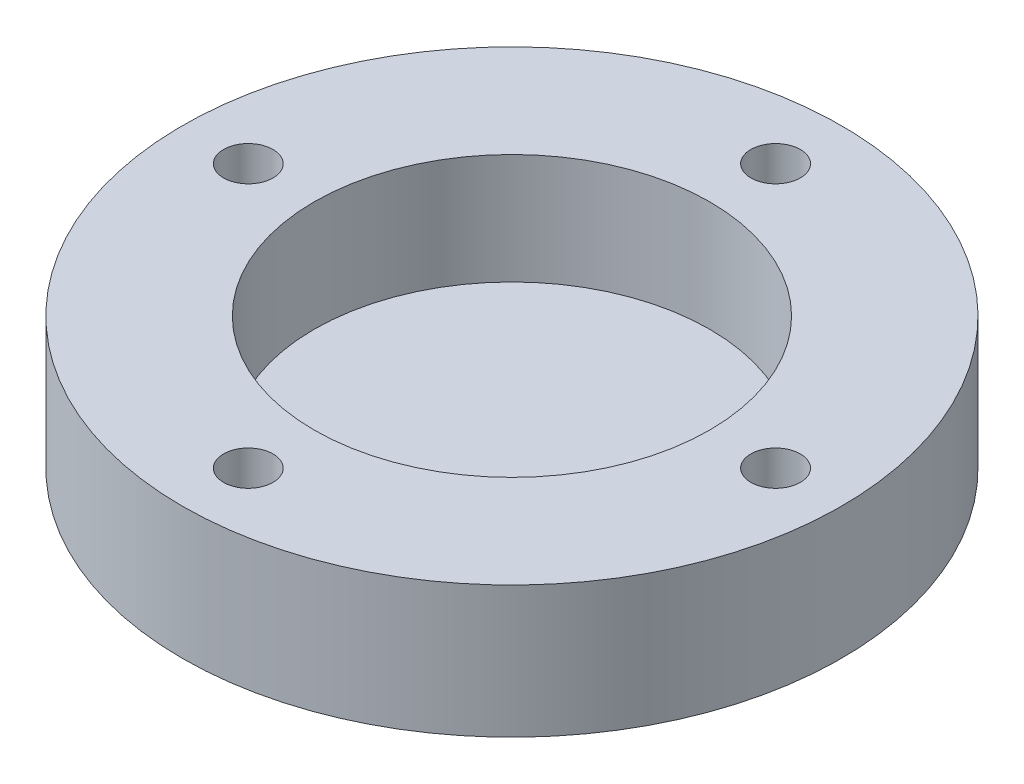
SolidWorks part; units mm, degrees
ref_plane "Front Plane" through (0, 0, 0) normal (0, 0, 1) x (1, 0, 0)
ref_plane "Top Plane" through (0, 0, 0) normal (0, 1, 0) x (1, 0, 0)
ref_plane "Right Plane" through (0, 0, 0) normal (1, 0, 0) x (0, 0, -1)
sketch "Sketch2" plane through (0, 0, 0) normal (0, 1, 0) x (1, 0, 0)
  circle A0 centre (0, 0) radius 20
  dimension "D1" = 40
extrude "Boss-Extrude1" add sketch "Sketch2" along normal blind 8
sketch "Sketch3" plane through (0, 8, 0) normal (0, 1, 0) x (1, 0, 0)
  line L0 (0, 0) -> (0, 16) construction
  line L1 (0, 36.0452) -> (0, 0) construction
  line L2 (0, 0) -> (29.8804, 0) construction
  line L3 (-16, 0) -> (0, 0) construction
  line L4 (16, 0) -> (0, 0) construction
  line L5 (0, 16) -> (0, 0) construction
  line L6 (0, 0) -> (0, -16) construction
  circle A1 centre (0, 16) radius 1.5
  circle A2 centre (-16, 0) radius 1.5
  circle A3 centre (16, 0) radius 1.5
  circle A4 centre (0, -16) radius 1.5
  dimension "D2" = 3
  dimension "D3" = 16
extrude "Cut-Extrude1" cut sketch "Sketch3" against normal through all
sketch "Sketch4" plane through (0, 8, -8) normal (0, -1, 0) x (1, 0, 0)
  circle A0 centre (0, 8) radius 12
  circle A5 centre (0, 8) radius 20 construction
  dimension "D1" = 24
extrude "Cut-Extrude2" cut sketch "Sketch4" along normal blind 6.7
